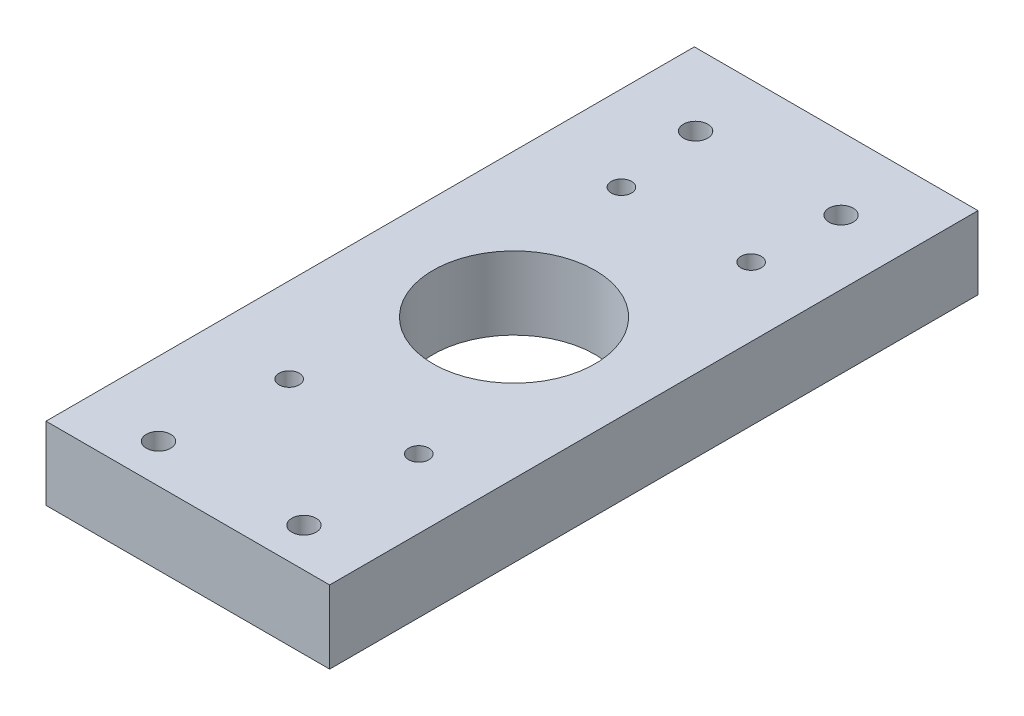
SolidWorks part; units mm, degrees
ref_plane "Front Plane" through (0, 0, 0) normal (0, 0, 1) x (1, 0, 0)
ref_plane "Top Plane" through (0, 0, 0) normal (0, 1, 0) x (1, 0, 0)
ref_plane "Right Plane" through (0, 0, 0) normal (1, 0, 0) x (0, 0, -1)
sketch "Sketch1" plane through (0, 0, 0) normal (0, 1, 0) x (1, 0, 0)
  line L1 (-35, 80) -> (35, 80)
  line L2 (-35, 80) -> (-35, -80)
  line L3 (-35, -80) -> (35, -80)
  line L4 (35, 80) -> (35, -80)
  line L5 (-35, 80) -> (35, -80) construction
  line L6 (-35, -80) -> (35, 80) construction
  point P0 (0, 0)
  dimension "D1" = 160
  dimension "D2" = 70
extrude "Boss-Extrude1" add sketch "Sketch1" along normal blind 18
sketch "Sketch2" plane through (0, 18, 0) normal (0, 1, 0) x (1, 0, 0)
  circle A0 centre (0.5, 0.0018) radius 20
  circle A1 centre (0.5, 0.0018) radius 4 construction
  dimension "D1" = 0
  dimension "D2" = 40
extrude "Cut-Extrude1" cut sketch "Sketch2" against normal through all
hole_wizard "Ø6.0 (6) Diameter Hole1" positions "Sketch4" profile "Sketch3" hole size "Ø6.0" standard "ISO" end condition through all
sketch "Sketch4" plane through (0, 18, 0) normal (0, 1, 0) x (1, 0, 0)
  point P0 (19.0691, 62.1356)
  point P2 (-16.8246, 62.1356)
  point P4 (19.0691, -70.413)
  point P6 (-16.8246, -70.413)
sketch "Sketch3" plane through (19.0691, 18, -62.1356) normal (1, 0, 0) x (0, 0, 1)
  line L0 (0, 0) -> (0, 18)
  line L1 (0, 18) -> (3, 18)
  line L2 (3, 18) -> (3, 0)
  line L5 (3, 0) -> (0, 0)
  line L11 (0, -6.35) -> (0, 107.95) construction
  dimension "Thru Hole Dia." = 6
  dimension "Thru Hole Depth" = 18
hole_wizard "Ø4.0 (4) Diameter Hole1" positions "Sketch6" profile "Sketch5" hole size "Ø4.0" standard "ISO"
sketch "Sketch6" plane through (-35, 0, 0) normal (-1, 0, 0) x (0, 0, 1)
  line L0 (-80, 0) -> (80, 0) construction
  line L1 (80, 18) -> (80, 0) construction
  point P0 (28, 9)
  point P2 (-28, 9)
  dimension "D1" = 9
  dimension "D2" = 9
  dimension "D3" = 56
  dimension "D4" = 52
sketch "Sketch5" plane through (-35, 9, 28) normal (0, 1, 0) x (0, 0, 1)
  line L0 (0, 0) -> (0, 30)
  line L1 (0, 30) -> (2, 30)
  line L2 (2, 30) -> (2, 0)
  line L5 (2, 0) -> (0, 0)
  line L10 (0, 30) -> (-2, 30) construction
  line L11 (0, -6.35) -> (0, 107.95) construction
  dimension "Hole Dia." = 4
  dimension "Hole Depth" = 30
  dimension "Drill Angle" = 180
hole_wizard "Ø5.0 (5) Diameter Hole1" positions "Sketch8" profile "Sketch7" hole size "Ø5.0" standard "ISO" end condition through all
sketch "Sketch8" plane through (0, 18, 0) normal (0, 1, 0) x (1, 0, 0)
  line L0 (35, -50) -> (-35, -50) construction
  line L1 (35, 50) -> (-35, 50) construction
  line L2 (-35, 80) -> (-35, -80) construction
  point P0 (18, 41)
  point P2 (-14, 41)
  point P4 (18, -41)
  point P6 (-14, -41)
  dimension "D1" = 9
  dimension "D2" = 9
  dimension "D3" = 9
  dimension "D4" = 9
  dimension "D5" = 32
  dimension "D6" = 32
  dimension "D7" = 21
  dimension "D8" = 21
sketch "Sketch7" plane through (18, 18, -41) normal (1, 0, 0) x (0, 0, 1)
  line L0 (0, 0) -> (0, 18)
  line L1 (0, 18) -> (2.5, 18)
  line L2 (2.5, 18) -> (2.5, 0)
  line L5 (2.5, 0) -> (0, 0)
  line L11 (0, -6.35) -> (0, 107.95) construction
  dimension "Thru Hole Dia." = 5
  dimension "Thru Hole Depth" = 18
